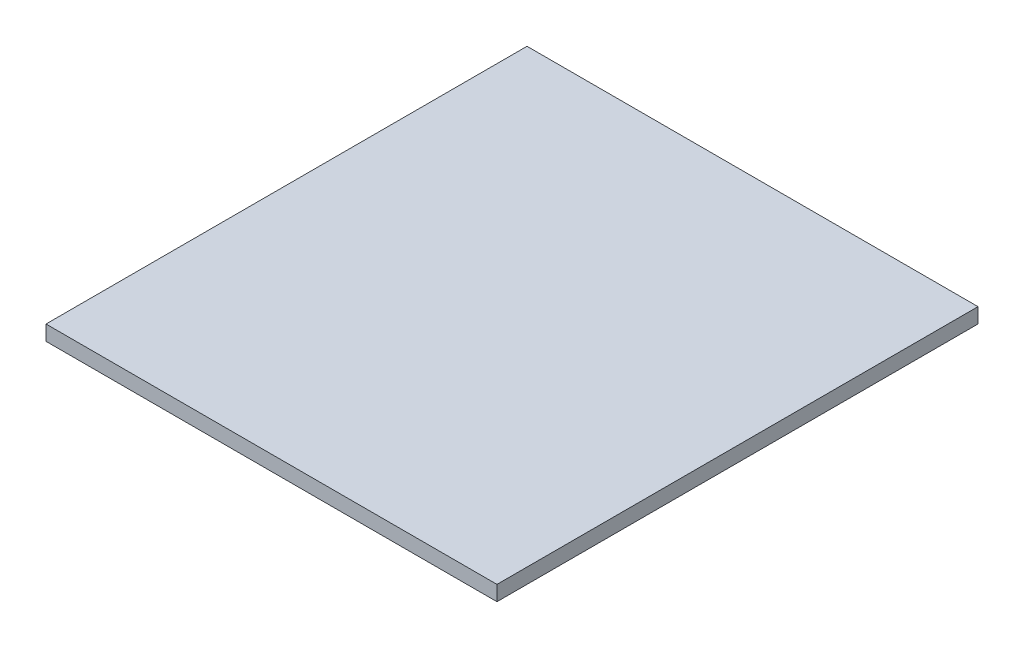
SolidWorks part; units mm, degrees
ref_plane "Front Plane" through (0, 0, 0) normal (0, 0, 1) x (1, 0, 0)
ref_plane "Top Plane" through (0, 0, 0) normal (0, 1, 0) x (1, 0, 0)
ref_plane "Right Plane" through (0, 0, 0) normal (1, 0, 0) x (0, 0, -1)
sketch "Sketch1" plane through (0, 0, 0) normal (0, 1, 0) x (1, 0, 0)
  line L1 (-158.75, 165.1) -> (158.75, 165.1)
  line L2 (-158.75, 165.1) -> (-158.75, -165.1)
  line L3 (-158.75, -165.1) -> (158.75, -165.1)
  line L4 (158.75, 165.1) -> (158.75, -165.1)
  line L5 (-158.75, 165.1) -> (158.75, -165.1) construction
  line L6 (-158.75, -165.1) -> (158.75, 165.1) construction
  point P0 (0, 0)
  dimension "D1" = 317.5
  dimension "D2" = 330.2
ref_plane "Plane1" through (0, 25.4, 0) normal (0, 1, 0) x (1, 0, 0)
sketch "Sketch2" plane through (0, 25.4, 0) normal (0, 1, 0) x (1, 0, 0)
  line L1 (-163.83, 176.53) -> (163.83, 176.53)
  line L2 (-163.83, 176.53) -> (-163.83, -176.53)
  line L3 (-163.83, -176.53) -> (163.83, -176.53)
  line L4 (163.83, 176.53) -> (163.83, -176.53)
  line L5 (-163.83, 176.53) -> (163.83, -176.53) construction
  line L6 (-163.83, -176.53) -> (163.83, 176.53) construction
  point P0 (0, 0)
  dimension "D1" = 327.66
  dimension "D2" = 353.06
loft "Loft1" add profiles "Sketch1", "Sketch2"
sketch "Sketch4" plane through (0, 25.4, 0) normal (0, 1, 0) x (1, 0, 0)
  line L1 (-190.5, 203.2) -> (190.5, 203.2)
  line L2 (-190.5, 203.2) -> (-190.5, -203.2)
  line L3 (-190.5, -203.2) -> (190.5, -203.2)
  line L4 (190.5, 203.2) -> (190.5, -203.2)
  line L5 (-190.5, 203.2) -> (190.5, -203.2) construction
  line L6 (-190.5, -203.2) -> (190.5, 203.2) construction
  point P0 (0, 0)
  dimension "D1" = 381
  dimension "D2" = 406.4
extrude "Boss-Extrude1" add sketch "Sketch4" along normal blind 12.7
